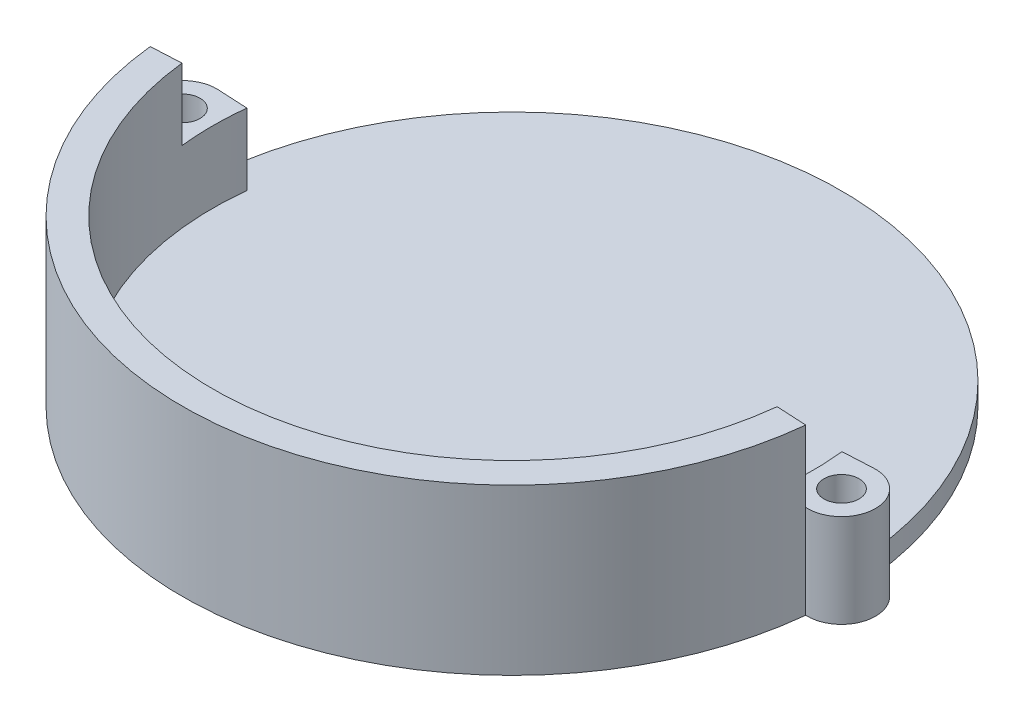
SolidWorks part; units mm, degrees
ref_plane "Front Plane" through (0, 0, 0) normal (0, 0, 1) x (1, 0, 0)
ref_plane "Top Plane" through (0, 0, 0) normal (0, 1, 0) x (1, 0, 0)
ref_plane "Right Plane" through (0, 0, 0) normal (1, 0, 0) x (0, 0, -1)
sketch "Sketch1" plane through (0, 0, 0) normal (0, 1, 0) x (1, 0, 0)
  circle A0 centre (0, 0) radius 30
  dimension "D1" = 60
extrude "Boss-Extrude1" add sketch "Sketch1" along normal blind 2
sketch "Sketch2" plane through (0, 2, 0) normal (0, 1, 0) x (1, 0, 0)
  circle A0 centre (0, 0) radius 27.1
  circle A1 centre (0, 0) radius 27.25
  circle A2 centre (0, 0) radius 32.5
  dimension "D1" = 54.5
  dimension "D2" = 54.2
extrude "Boss-Extrude2" add sketch "Sketch2" along normal blind 13
sketch "Sketch3" plane through (0, 0, 0) normal (0, -1, 0) x (1, 0, 0)
  circle A5 centre (0, 0) radius 5
  dimension "D1" = 10
extrude "Cut-Extrude2" [suppressed] cut sketch "Sketch3" against normal up to next contours A5
sketch "Sketch5" plane through (0, 0, 0) normal (0, -1, 0) x (1, 0, 0)
  line L1 (-9, -5.5) -> (9, -5.5) construction
  line L2 (-9, -5.5) -> (-9, 5.5) construction
  line L3 (-9, 5.5) -> (9, 5.5) construction
  line L4 (9, -5.5) -> (9, 5.5) construction
  line L5 (-9, -5.5) -> (9, 5.5) construction
  line L6 (-9, 5.5) -> (9, -5.5) construction
  circle A0 centre (9, 5.5) radius 1.3
  circle A1 centre (9, -5.5) radius 1.3
  circle A2 centre (-9, -5.5) radius 1.3
  circle A3 centre (-9, 5.5) radius 1.3
  point P0 (0, 0)
  dimension "D1" = 2.6
  dimension "D2" = 18
  dimension "D3" = 11
extrude "Cut-Extrude3" [suppressed] cut sketch "Sketch5" against normal up to next
sketch "Sketch6" plane through (0, 15, 0) normal (0, 1, 0) x (1, 0, 0)
  line L0 (-8.25, 0) -> (8.25, 0) construction
  line L1 (35.8547, 0) -> (-34.5001, 0)
  line L2 (35.8547, 0) -> (35.8547, 43.3336)
  line L3 (35.8547, 43.3336) -> (-34.5001, 43.3336)
  line L4 (-34.5001, 0) -> (-34.5001, 43.3336)
  point P6 (-34.5001, 43.3336)
extrude "Cut-Extrude4" cut sketch "Sketch6" against normal up to surface (13 mm away) up to face at (0, 2, 27.25)
sketch "Sketch7" plane through (0, 2, 0) normal (0, 1, 0) x (1, 0, 0)
  line L1 (-29.8398, -3.0959) -> (-27.1045, -2.8121)
  line L2 (-27.0895, 2.9536) -> (-29.8398, 3.0959)
  arc A0 (-27.0895, 2.9536) -> (-27.1045, -2.8121) centre (0, 0) ccw
  circle A2 centre (-30, 0) radius 1.6 construction
  circle A3 centre (-30, 0) radius 3.1 construction
  arc A4 (-29.8398, -3.0959) -> (-29.8398, 3.0959) centre (-30, 0) cw
  arc A6 (-27.25, 0) -> (27.25, 0) centre (0, 0) ccw construction
  arc A8 (-30, 0) -> (30, 0) centre (0, 0) ccw construction
  arc A9 (30, 0) -> (-30, 0) centre (0, 0) ccw construction
  point P1 (-27.8607, 2.9255)
  point P12 (-29.8398, -3.0959)
  point P18 (-29.8398, 3.0959)
  point P22 (0, 0)
  dimension "D1" = 3.2
  dimension "D2" = 1.5
extrude "Boss-Extrude3" add sketch "Sketch7" along normal blind 6.5
sketch "Sketch8" plane through (0, 15, 0) normal (0, 1, 0) x (1, 0, 0)
  circle A0 centre (-30, 0) radius 1.6
  dimension "D1" = 3.2
extrude "Cut-Extrude5" cut sketch "Sketch8" against normal through all
sketch "Sketch9" plane through (0, 15, 0) normal (0, 1, 0) x (1, 0, 0)
  line L0 (-29.8398, -3.0959) -> (27.2496, -0.1423)
  line L1 (27.2496, -0.1423) -> (-26.8769, 0)
  line L2 (-8.25, 0) -> (8.25, 0) construction
  line L3 (-26.8769, 0) -> (-30.3873, 0)
  line L4 (-30.3873, 0) -> (-29.8398, -3.0959)
  arc A0 (-27.0895, 2.9536) -> (27.25, 0) centre (0, 0) ccw construction
  arc A2 (-29.9573, -1.5994) -> (30, 0) centre (0, 0) ccw construction
  arc A3 (-29.9573, -1.5994) -> (-29.8398, -3.0959) centre (0, 0) ccw construction
  arc A4 (-29.8398, 3.0959) -> (-29.8398, -3.0959) centre (-30, 0) ccw construction
  point P6 (-29.8398, 3.0959)
  point P14 (-27.2072, 1.5261)
  point P15 (-27.2072, 1.5261)
  point P16 (0, 0)
  point P17 (-29.8398, 3.0959)
  point P24 (-26.9253, 4.4353)
  point P27 (-26.8769, 0)
  point P28 (-29.8398, 0)
  point P29 (-29.8398, 0)
  point P30 (-29.8398, 0)
  point P31 (-29.8398, 0)
  point P32 (-30.3873, 0)
extrude "Cut-Extrude6" cut sketch "Sketch9" against normal up to surface (6.5 mm away) up to face at (-29.609, 8.5, -0.5452)
mirror "Mirror1" [suppressed] about plane through (0, 0, 0) normal (1, 0, 0)
sketch "Sketch10" plane through (0, 0, 0) normal (0, -1, 0) x (1, 0, 0)
  line L0 (-29.8398, -3.0959) -> (-27.7681, -1.6)
  line L1 (-27.7681, -1.6) -> (-27.7681, 1.4216)
  line L2 (-27.7681, 1.4216) -> (-29.8398, 3.0959)
  line L3 (0, -8.25) -> (0, 8.25) construction
  line L4 (27.7681, 1.4216) -> (29.8398, 3.0959)
  line L5 (27.7681, -1.6) -> (27.7681, 1.4216)
  line L6 (29.8398, -3.0959) -> (27.7681, -1.6)
  arc A3 (-29.8398, -3.0959) -> (-29.8398, 3.0959) centre (-30, 0) cw
  circle A4 centre (-30, 0) radius 1.6
  circle A5 centre (30, 0) radius 1.6
  arc A6 (29.8398, -3.0959) -> (29.8398, 3.0959) centre (30, 0) ccw
extrude "Boss-Extrude4" add sketch "Sketch10" against normal up to surface (2 mm away) up to face at (-31.129, 2, 0)
mirror "Mirror2" about plane through (0, 0, 0) normal (1, 0, 0) of "Cut-Extrude5", "Boss-Extrude3", "Cut-Extrude6"
